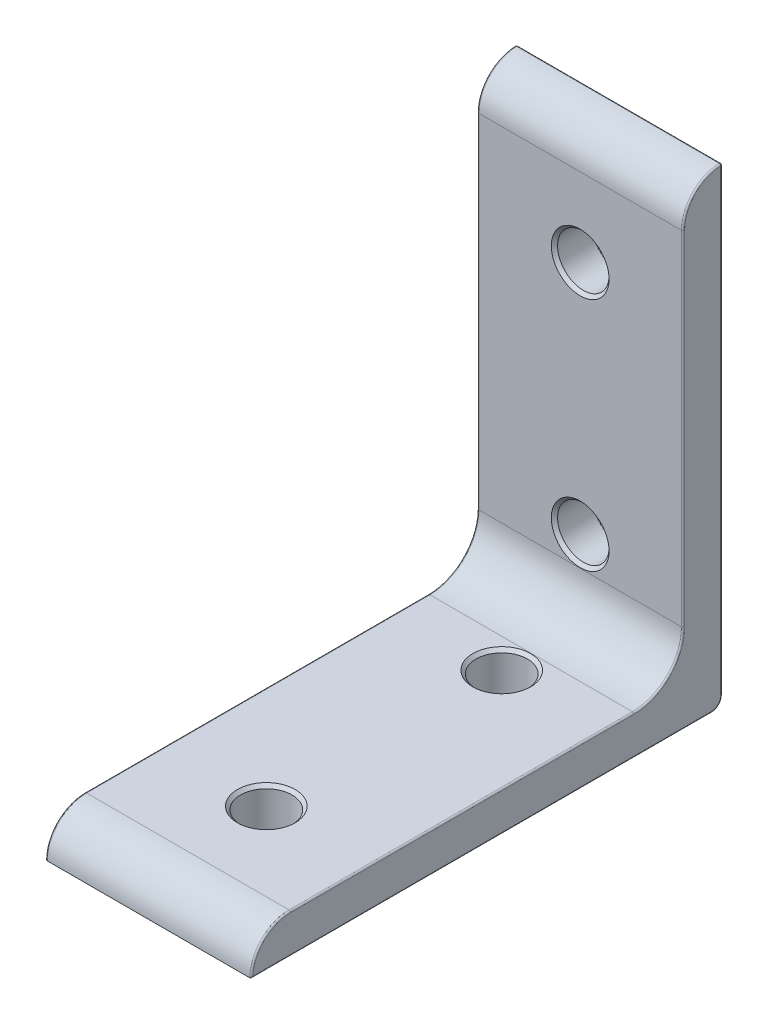
SolidWorks part; units mm, degrees
ref_plane "Front Plane" through (0, 0, 0) normal (0, 0, 1) x (1, 0, 0)
ref_plane "Top Plane" through (0, 0, 0) normal (0, 1, 0) x (1, 0, 0)
ref_plane "Right Plane" through (0, 0, 0) normal (1, 0, 0) x (0, 0, -1)
sketch "Sketch1" plane through (0, 0, 0) normal (0, 0, 1) x (1, 0, 0)
  line L0 (-16.637, -38.1) -> (16.637, -38.1) construction
  line L1 (0, -38.1) -> (0, 38.1) construction
  line L2 (-16.637, 38.1) -> (16.637, 38.1) construction
  dimension "Width" = 33.274
  dimension "Length" = 76.2
sketch "Sketch2" plane through (0, 0, 0) normal (1, 0, 0) x (0, 0, -1)
  line L0 (-69.85, -38.1) -> (6.35, -38.1) construction
  line L1 (0, -38.1) -> (0, 38.1) construction
  line L2 (6.35, -38.1) -> (6.35, 38.1) construction
  line L3 (0, 31.75) -> (0, -23.8125)
  line L4 (-7.9375, -31.75) -> (-63.5, -31.75)
  line L5 (6.35, -19.05) -> (0, -19.05) construction
  line L6 (-12.7, -38.1) -> (-12.7, -31.75) construction
  line L7 (6.35, -14.8844) -> (6.35, -23.2156)
  line L8 (-16.8656, -38.1) -> (-8.5344, -38.1)
  line L9 (6.35, -19.05) -> (17.4752, -19.05) construction
  line L10 (17.4752, -15.0812) -> (17.4752, -23.0187) construction
  line L11 (6.35, 23.2156) -> (6.35, 14.8844)
  line L12 (-54.9656, -38.1) -> (-46.6344, -38.1)
  arc A0 (6.35, 38.1) -> (0, 31.75) centre (6.35, 31.75) ccw
  arc A1 (0, -23.8125) -> (-7.9375, -31.75) centre (-7.9375, -23.8125) cw
  arc A2 (-63.5, -31.75) -> (-69.85, -38.1) centre (-63.5, -38.1) ccw
  point P28 (-50.8, -38.1)
  point P30 (6.35, 19.05)
  dimension "Bracket End Radius" = 6.35
  dimension "Bracket Corner Radius" = 7.9375
  dimension "Bracket Thickness" = 6.35
  dimension "Mounting Hole Diameter" = 8.3312
  dimension "Mounting Hole Center Offset" = 19.05
  dimension "D3" = 19.05
  dimension "Mounting Fastener Thread Length" = 17.4752
  dimension "Mounting Fastener Thread Size" = 7.9375
  dimension "Mounting Hole CtoC" = 38.1
  dimension "D5" = 38.1
sketch "Sketch3" plane through (0, 0, 0) normal (1, 0, 0) x (0, 0, -1)
  line L0 (-7.9375, -31.75) -> (-63.5, -31.75) construction
  line L1 (0, 31.75) -> (0, -23.8125) construction
  line L2 (-7.9375, -31.75) -> (-63.5, -31.75)
  line L3 (0, 31.75) -> (0, -23.8125)
  line L4 (-69.85, -38.1) -> (6.35, -38.1)
  line L5 (6.35, -38.1) -> (6.35, 38.1)
  arc A0 (-63.5, -31.75) -> (-69.85, -38.1) centre (-63.5, -38.1) ccw construction
  arc A1 (-7.9375, -31.75) -> (0, -23.8125) centre (-7.9375, -23.8125) ccw construction
  arc A2 (6.35, 38.1) -> (0, 31.75) centre (6.35, 31.75) ccw construction
  arc A3 (-63.5, -31.75) -> (-69.85, -38.1) centre (-63.5, -38.1) ccw
  arc A4 (-7.9375, -31.75) -> (0, -23.8125) centre (-7.9375, -23.8125) ccw
  arc A5 (6.35, 38.1) -> (0, 31.75) centre (6.35, 31.75) ccw
extrude "Boss-Extrude1" add sketch "Sketch3" against normal up to vertex (16.637 mm away) from vertex at 16.637 starting at point (16.637, -38.1, 0)
fillet "Fillet1" radius 1.6955 1 edges at (0, -38.1, -6.35)
sketch "Sketch4" plane through (0, 0, 0) normal (0, 0, 1) x (1, 0, 0)
  line L1 (0, -23.8125) -> (0, 31.75) construction
  line L2 (-16.637, -23.8125) -> (16.637, -23.8125) construction
  line L3 (-16.637, 31.75) -> (16.637, 31.75) construction
  line L4 (0, 23.2156) -> (0, 14.8844) construction
  circle A0 centre (0, 19.05) radius 4.1656
  circle A1 centre (0, -19.05) radius 4.1656
  point P21 (0, 19.05)
extrude "Cut-Extrude1" cut sketch "Sketch4" against normal through all
sketch "Sketch6" plane through (0, -31.75, 0) normal (0, 1, 0) x (1, 0, 0)
  line L0 (0, -7.9375) -> (0, -63.5) construction
  line L1 (0, -54.9656) -> (0, -46.6344) construction
  circle A0 centre (0, -12.7) radius 4.1656
  circle A1 centre (0, -50.8) radius 4.1656
extrude "Cut-Extrude3" cut sketch "Sketch6" against normal blind 7.874
chamfer "Chamfer1" distance 0.508 angle 45 4 edges at (4.1656, 19.05, 0) (-4.1656, -19.05, 0) (0, -31.75, 54.9656) (0, -31.75, 16.8656)
fillet "Fillet2" radius 0.254 19 edges at (-16.637, -38.1, 32.5977) (-16.637, -37.6034, -5.8534) (16.637, -38.1, 32.5977) (16.637, -37.6034, -5.8534) (-16.637, 36.2401, -1.8599) (-16.637, -33.6099, 67.9901) (-16.637, -31.75, 35.7188) (-16.637, -29.4252, 2.3248) (16.637, 36.2401, -1.8599) (16.637, -33.6099, 67.9901) (16.637, -31.75, 35.7188) (16.637, -29.4252, 2.3248) (0, 38.1, -6.35) (-16.637, 0.8477, -6.35) (16.637, 0.8477, -6.35) (-4.1656, -19.05, -6.35) (4.1656, 19.05, -6.35) (-16.637, 3.9688, 0) (16.637, 3.9688, 0)
equation "\"D3@Sketch2\" = \"Mounting Hole Center Offset@Sketch2\""
equation "\"D5@Sketch2\"=\"Mounting Hole CtoC@Sketch2\""
equation "\"D1@Fillet1\"=\"Bracket Thickness@Sketch2\"*.267"
